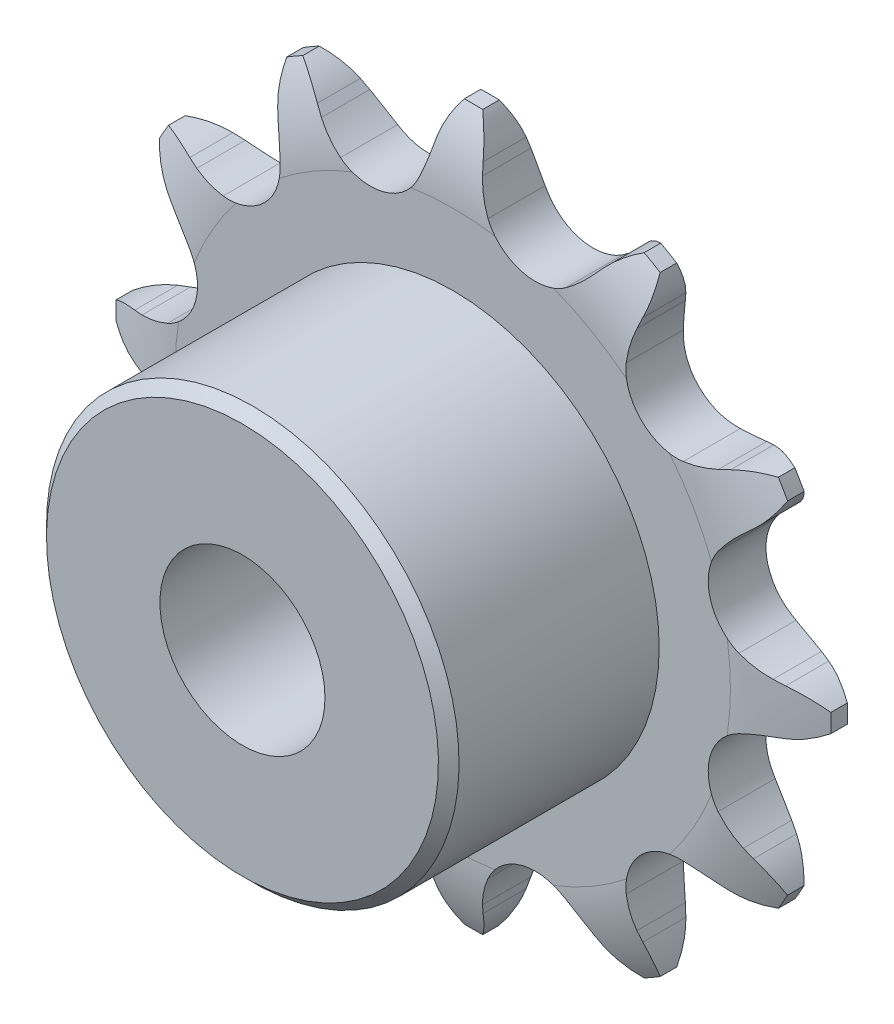
SolidWorks part; units mm, degrees
ref_plane "Front Plane" through (0, 0, 0) normal (0, 0, 1) x (1, 0, 0)
ref_plane "Top Plane" through (0, 0, 0) normal (0, 1, 0) x (1, 0, 0)
ref_plane "Right Plane" through (0, 0, 0) normal (1, 0, 0) x (0, 0, -1)
sketch "Sketch0" plane through (0, 0, 0) normal (0, 0, 1) x (1, 0, 0)
  line L0 (4, -14.9282) -> (0, 0) construction
  line L1 (0, 0) -> (10.9282, -10.9282) construction
  line L2 (0, 0) -> (-4, -14.9282) construction
  line L3 (4, -14.9282) -> (10.9282, -10.9282) construction
  line L4 (4, -14.9282) -> (-4, -14.9282) construction
  line L5 (6.9269, -14.2183) -> (6.5992, -13.85)
  line L6 (4, -14.9282) -> (0, -16) construction
  line L7 (1.1103, -15.7769) -> (1.21, -15.294)
  line L8 (0, -14.9282) -> (0, -17.3282) construction
  line L9 (5.463, -12.8389) -> (1.7057, -18.2048) construction
  line L10 (0, 0) -> (0, -14.9282) construction
  line L11 (6.5992, -13.85) -> (1.7057, -18.2048) construction
  line L12 (0, -17.3282) -> (0, -17.8633) construction
  line L13 (10.0622, -11.4282) -> (6.9269, -14.2183) construction
  circle A0 centre (0, 0) radius 17.3282 construction
  circle A1 centre (0, 0) radius 15.4548 construction
  arc A2 (-3.8269, -19.0429) -> (12.8356, -14.5782) centre (0, 0) ccw
  circle A3 centre (0, 0) radius 17.8633 construction
  circle A4 centre (4, -14.9282) radius 2.5 construction
  arc A7 (5.463, -12.8389) -> (1.6884, -13.8503) centre (4, -14.9282) ccw
  circle A8 centre (4, -14.9282) radius 2.5506 construction
  arc A9 (6.9269, -14.2183) -> (12.8356, -14.5782) centre (10.0622, -11.4282) ccw
  arc A10 (6.5992, -13.85) -> (5.463, -12.8389) centre (1.7057, -18.2048) ccw
  arc A11 (1.1103, -15.7769) -> (-3.8269, -19.0429) centre (-3, -14.9282) cw
  arc A12 (1.21, -15.294) -> (1.6884, -13.8503) centre (7.6252, -16.6187) cw
  dimension "D1" = 2.5506
  dimension "Dr" = 5
  dimension "Ds" = 5.1012
  dimension "R" = 2.5506
  dimension "Pitch" = 8
  dimension "A" = 40
  dimension "360/N" = 30
  dimension "B" = 13.333
  dimension "ab" = 7
  dimension "J" = 2.4
  dimension "ac" = 4
sketch "Sketch1" plane through (0, 0, 0) normal (1, 0, 0) x (0, 0, -1)
  line L0 (1.4, 0) -> (-1.4, 0)
  line L1 (-1.4, 0) -> (-1.4, 13.4552)
  line L2 (-1.4, 15.4548) -> (0, 15.4548) construction
  line L3 (-0.4, 17.3282) -> (0.4, 17.3282)
  line L5 (1.4, 13.4552) -> (1.4, 0)
  line L7 (0, 17.3282) -> (0, 0) construction
  line L8 (-1.4, 13.4552) -> (1.4, 13.4552) construction
  line L9 (0, 17.3282) -> (0, -17.3282) construction
  line L10 (-1.4, 13.4552) -> (-1.4, 17.3282) construction
  line L11 (-1.4, 17.3282) -> (-0.4, 17.3282) construction
  line L12 (0.4, 17.3282) -> (1.4, 17.3282) construction
  line L13 (1.4, 17.3282) -> (1.4, 13.4552) construction
  line L14 (0, 0) -> (-6.4008, 0) construction
  line L15 (-1.4, 15.4548) -> (-1.4, 10.1548) construction
  line L22 (1.4, 0) -> (-11.6, 0) construction
  line L24 (-1.4, 0) -> (-1.4, 10.1548) construction
  arc A0 (-0.4, 17.3282) -> (-1.4, 13.4552) centre (6.6, 13.4552) ccw
  arc A1 (0.4, 17.3282) -> (1.4, 13.4552) centre (-6.6, 13.4552) cw
  dimension "R" = 8
  dimension "t" = 2.8
  dimension "C" = 1
  dimension "A" = 3.873
  dimension "K" = 6.4008
  dimension "Width" = 13
  dimension "H" = 5.3
revolve "Revolve1" add sketch "Sketch1" angle 360 about L0
extrude "Cut-Extrude1" cut sketch "Sketch0" against normal through all and the other way through all
pattern_circular "CirPattern1" count 12 over 360 about axis through (0, 0, 0) along (0, 0, 1) of "Cut-Extrude1"
sketch "Sketch2" plane through (0, 0, 0) normal (0, 0, 1) x (1, 0, 0)
  circle A0 centre (0, 0) radius 4 construction
  circle A1 centre (0, 0) radius 10
  circle A2 centre (0, 0) radius 17.33 construction
  dimension "Bore" = 8
  dimension "Hub Dia." = 20
  dimension "OD" = 34.66
extrude "Boss-Extrude1" add sketch "Sketch2" along normal up to vertex (11.6 mm away) from surface at 1.4 starting at face at (0, 0, 1.4)
sketch "Sketch3" plane through (0, 0, 0) normal (0, 0, 1) x (1, 0, 0)
  circle A0 centre (0, 0) radius 4 construction
  circle A1 centre (0, 0) radius 4
extrude "Cut-Extrude2" cut sketch "Sketch3" along normal through all and the other way through all
sketch "Sketch4" plane through (0, 0, 0) normal (1, 0, 0) x (0, 0, -1)
  line L0 (-11.6, 10) -> (-11.6, 9.5)
  line L1 (-1.4, 17.3282) -> (-3.5, 17.3282)
  line L2 (-1.4, 17.3282) -> (-1.4, 10.1548)
  line L3 (-1.4, 10.1548) -> (-3.5, 10.1548)
  line L4 (-3.5, 17.3282) -> (-3.5, 10.1548)
  line L9 (-11.6, 9.5) -> (-11.1, 10)
  line L10 (-11.1, 10) -> (-11.6, 10)
  dimension "C" = 0.5
  dimension "D3" = 2.1
revolve "Cut-Revolve1" cut sketch "Sketch4" angle 360 about L22
sketch "Sketch5" plane through (0, 0, 0) normal (0, 0, 1) x (1, 0, 0)
  circle A0 centre (0, 0) radius 17.33 construction
  circle A1 centre (0, 0) radius 17.33
extrude "Cut-Extrude3" [suppressed] cut sketch "Sketch5" against normal through all and the other way through all flip side to cut
equation "\"360/N@Sketch0\" = 360/\"Teeth@CirPattern1\""
equation "\"Ds@Sketch0\" = 1.005 * \"Dr@Sketch0\" + ( 0.003 * 25.4 ) "
equation "\"R@Sketch0\" = 1/2 * \"Ds@Sketch0\""
equation "\"A@Sketch0\" = 35 +  ( 60 / \"Teeth@CirPattern1\" ) "
equation "\"B@Sketch0\" = 18 -  ( 56 / \"Teeth@CirPattern1\" )"
equation "\"ac@Sketch0\" = 0.8 * \"Dr@Sketch0\""
equation "\"ab@Sketch0\" = 1.4 * \"Dr@Sketch0\""
equation "\"J@Sketch0\" = 0.3 * \"Pitch@Sketch0\""
equation "\"D3@Sketch4\" = \"t@Sketch1\" * 3 / 4"
